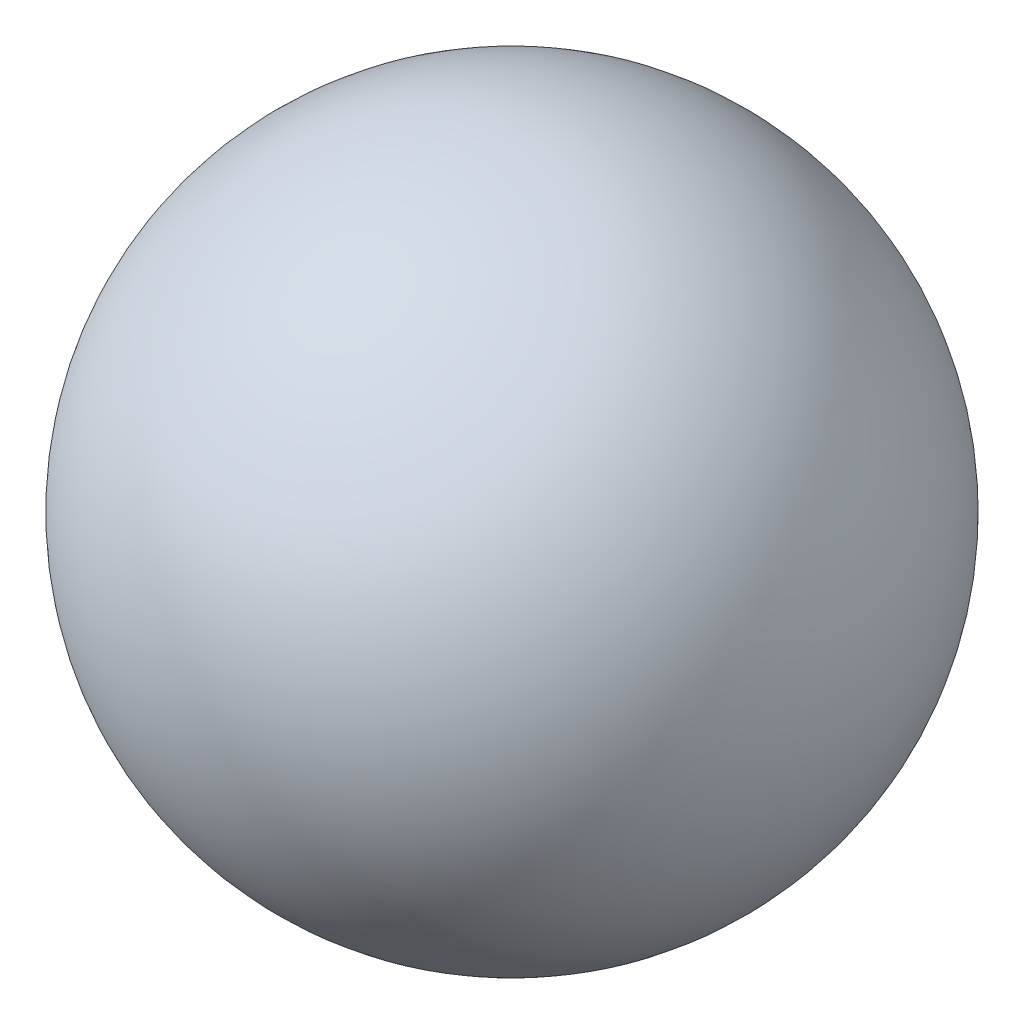
SolidWorks part; units mm, degrees
ref_plane "Front Plane" through (0, 0, 0) normal (0, 0, 1) x (1, 0, 0)
ref_plane "Top Plane" through (0, 0, 0) normal (0, 1, 0) x (1, 0, 0)
ref_plane "Right Plane" through (0, 0, 0) normal (1, 0, 0) x (0, 0, -1)
sketch "Sketch1" plane through (0, 0, 0) normal (0, 0, 1) x (1, 0, 0)
  line L0 (0, -12.7) -> (0, 12.7)
  arc A0 (0, 12.7) -> (0, -12.7) centre (0, 0) cw
  point P4 (0, 0)
  dimension "D1" = 25.4
revolve "Revolve1" add sketch "Sketch1" angle 360 about L0
